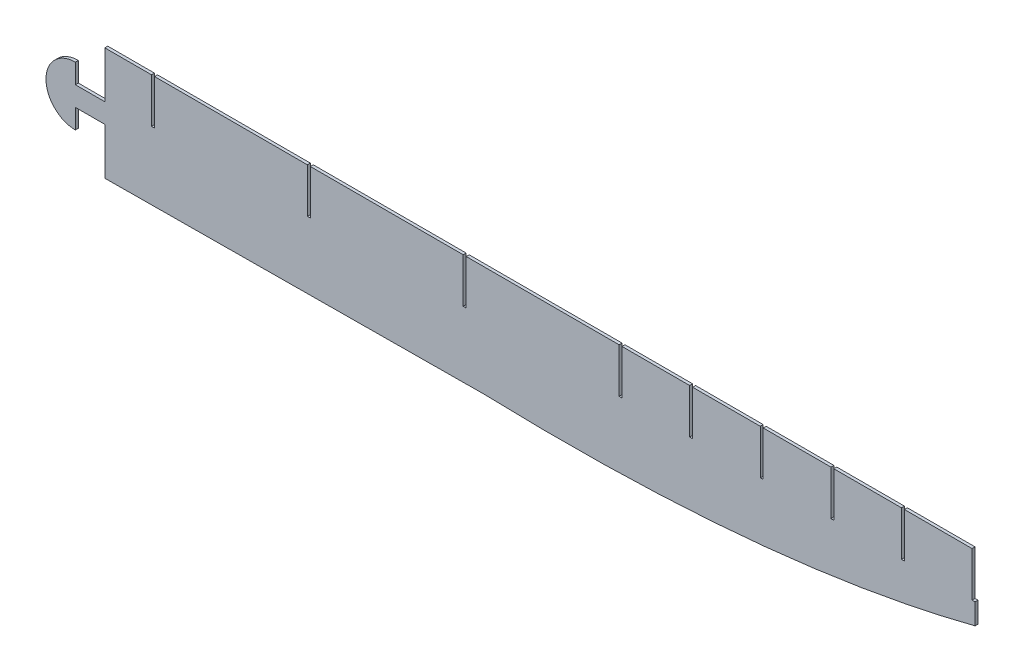
SolidWorks part; units mm, degrees
ref_plane "Front Plane" through (0, 0, 0) normal (0, 0, 1) x (1, 0, 0)
ref_plane "Top Plane" through (0, 0, 0) normal (0, 1, 0) x (1, 0, 0)
ref_plane "Right Plane" through (0, 0, 0) normal (1, 0, 0) x (0, 0, -1)
sketch "Model" plane through (0, 0, 0) normal (0, 0, 1) x (1, 0, 0)
  line L0 (1130.2, -228.0527) -> (1130.2, -248.0527)
  line L1 (1130.2, -268.0527) -> (1130.2, -288.0527)
  line L2 (1160.2, -268.0527) -> (1130.2, -268.0527)
  line L3 (1160.2, -268.0527) -> (1160.2, -315.6796)
  line L4 (2048.1136, -245.9797) -> (2048.1136, -267.2367)
  line L5 (2048.1136, -245.9797) -> (2045.1136, -245.9797)
  line L6 (2045.1136, -200.4227) -> (2045.1136, -245.9797)
  line L7 (2045.1136, -200.4227) -> (1976.0711, -200.4227)
  line L8 (1976.0711, -245.9797) -> (1976.0711, -200.4227)
  line L9 (1976.0711, -245.9797) -> (1973.0711, -245.9797)
  line L10 (1973.0711, -200.4227) -> (1973.0711, -245.9797)
  line L11 (1973.0711, -200.4227) -> (1904.0286, -200.4227)
  line L12 (1904.0286, -245.9797) -> (1904.0286, -200.4227)
  line L13 (1904.0286, -245.9797) -> (1901.0286, -245.9797)
  line L14 (1901.0286, -200.4227) -> (1901.0286, -245.9797)
  line L15 (1901.0286, -200.4227) -> (1831.986, -200.4227)
  line L16 (1831.986, -245.9797) -> (1831.986, -200.4227)
  line L17 (1831.986, -245.9797) -> (1828.986, -245.9797)
  line L18 (1828.986, -200.4227) -> (1828.986, -245.9797)
  line L19 (1828.986, -200.4227) -> (1759.9435, -200.4227)
  line L20 (1759.9435, -245.9797) -> (1759.9435, -200.4227)
  line L21 (1759.9435, -245.9797) -> (1756.9435, -245.9797)
  line L22 (1756.9435, -200.4227) -> (1756.9435, -245.9797)
  line L23 (1756.9435, -200.4227) -> (1687.901, -200.4227)
  line L24 (1687.901, -245.9797) -> (1687.901, -200.4227)
  line L25 (1687.901, -245.9797) -> (1684.901, -245.9797)
  line L26 (1684.901, -200.4227) -> (1684.901, -245.9797)
  line L27 (1684.901, -200.4227) -> (1528.901, -200.4227)
  line L28 (1528.901, -245.9797) -> (1528.901, -200.4227)
  line L29 (1528.901, -245.9797) -> (1525.901, -245.9797)
  line L30 (1525.901, -200.4227) -> (1525.901, -245.9797)
  line L31 (1525.901, -200.4227) -> (1369.901, -200.4227)
  line L32 (1369.901, -245.9797) -> (1369.901, -200.4227)
  line L33 (1369.901, -245.9797) -> (1366.901, -245.9797)
  line L34 (1366.901, -200.4227) -> (1366.901, -245.9797)
  line L35 (1366.901, -200.4227) -> (1210.901, -200.4227)
  line L36 (1210.901, -245.9797) -> (1210.901, -200.4227)
  line L37 (1210.901, -245.9797) -> (1207.901, -245.9797)
  line L38 (1207.901, -200.4227) -> (1207.901, -245.9797)
  line L39 (1207.901, -200.4227) -> (1160.2, -200.4227)
  line L40 (1160.2, -200.4227) -> (1160.2, -248.0527)
  line L41 (1130.2, -248.0527) -> (1160.2, -248.0527)
  arc A0 (1130.2, -228.0527) -> (1130.2, -288.0527) centre (1130.2, -258.0527) ccw
  spline S0 degree 3 poles (1545.731, -313) (1417.2198, -313.7868) (1288.7096, -314.6867) (1160.2, -315.6796) knots 0 0 0 0 1 1 1 1
  spline S1 degree 3 poles (2048.1136, -267.2367) (1921.1161, -299.876) (1758.3765, -319.6381) (1545.731, -313) knots 0.571508 0.571508 0.571508 0.571508 1 1 1 1
extrude "Boss-Extrude1" add sketch "Model" along normal blind 3
